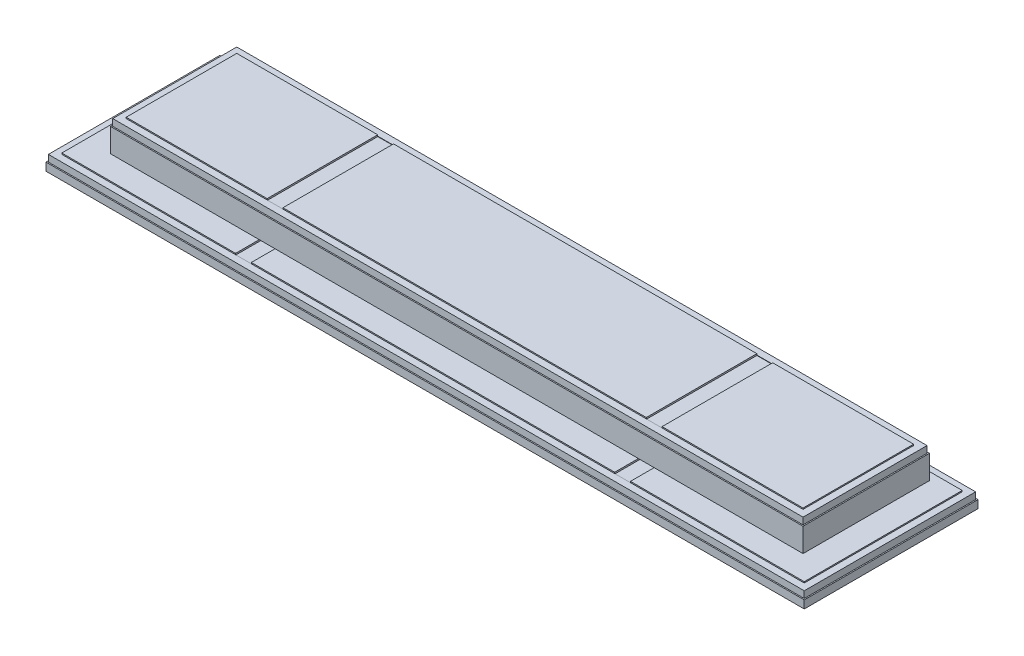
SolidWorks part; units mm, degrees
ref_plane "Front Plane" through (0, 0, 0) normal (0, 0, 1) x (1, 0, 0)
ref_plane "Top Plane" through (0, 0, 0) normal (0, 1, 0) x (1, 0, 0)
ref_plane "Right Plane" through (0, 0, 0) normal (1, 0, 0) x (0, 0, -1)
sketch "Sketch1" plane through (0, 0, 0) normal (0, 1, 0) x (1, 0, 0)
  line L0 (960, -210) -> (-960, -210)
  line L5 (960, -210) -> (960, 230)
  line L6 (-960, -210) -> (-960, 230)
  line L10 (960, 230) -> (-960, 230)
  point P0 (0, 0)
extrude "Boss-Extrude1" add sketch "Sketch1" along normal blind 40
ref_plane "Plane1" through (0, 40, 0) normal (0, 1, 0) x (1, 0, 0)
sketch "Sketch4" plane through (0, 40, 0) normal (0, 1, 0) x (1, 0, 0)
  line L7 (-960, -130) -> (960, -130)
  line L8 (-877, -130) -> (877, -130)
  line L13 (-877, 230) -> (-877, -210)
  line L14 (-877, 190) -> (-877, -130)
  line L17 (877, -210) -> (877, 230)
  line L19 (877, -130) -> (877, 190)
  line L21 (960, 190) -> (-960, 190)
  line L22 (877, 190) -> (-877, 190)
  dimension "D1" = 80
  dimension "D2" = 83
  dimension "D3" = 83
  dimension "D4" = 40
extrude "Boss-Extrude2" add sketch "Sketch4" along normal blind 80
ref_plane "Plane2" through (0, 120, 0) normal (0, 1, 0) x (1, 0, 0)
sketch "Sketch5" plane through (0, 120, 0) normal (0, 1, 0) x (1, 0, 0)
  line L0 (-857, -110) -> (857, -110)
  line L1 (857, -110) -> (857, 170)
  line L2 (857, 170) -> (-857, 170)
  line L3 (-857, 170) -> (-857, -110)
  line L4 (877, -130) -> (877, 190)
  line L5 (877, 190) -> (-877, 190)
  line L6 (-877, 190) -> (-877, -130)
  line L7 (-877, -130) -> (877, -130)
  line L8 (877, -130) -> (877, 190)
  line L9 (877, 190) -> (-877, 190)
  line L10 (-877, 190) -> (-877, -130)
  line L11 (-877, -130) -> (877, -130)
  dimension "D1" = 0
  dimension "D2" = 20
extrude "Cut-Extrude1" cut sketch "Sketch5" against normal blind 3
sketch "Sketch6" plane through (0, 120, 0) normal (0, 1, 0) x (1, 0, 0)
  line L0 (-874, -127) -> (874, -127)
  line L1 (874, -127) -> (874, 187)
  line L2 (874, 187) -> (-874, 187)
  line L3 (-874, 187) -> (-874, -127)
  line L4 (-877, -130) -> (877, -130)
  line L5 (877, -130) -> (877, 190)
  line L6 (877, 190) -> (-877, 190)
  line L7 (-877, 190) -> (-877, -130)
  line L8 (-877, -130) -> (877, -130)
  line L9 (877, -130) -> (877, 190)
  line L10 (877, 190) -> (-877, 190)
  line L11 (-877, 190) -> (-877, -130)
  dimension "D1" = 0
  dimension "D2" = 3
extrude "Cut-Extrude2" cut sketch "Sketch6" against normal blind 20
sketch "Sketch7" plane through (0, 120, 0) normal (0, 1, 0) x (1, 0, 0)
  line L0 (857, -110) -> (857, 170) construction
  line L1 (857, -110) -> (857, 170) construction
  line L2 (-857, 170) -> (-857, -110) construction
  line L3 (-857, 170) -> (-857, -110) construction
  line L4 (500, -110) -> (500, 170)
  line L5 (-500, 170) -> (-500, -110)
  line L6 (460, -110) -> (460, 170)
  line L7 (-460, 170) -> (-460, -110)
  line L8 (500, -110) -> (460, -110)
  line L9 (500, 170) -> (460, 170)
  line L10 (-460, -110) -> (-500, -110)
  line L11 (-460, 170) -> (-500, 170)
  dimension "D1" = 357
  dimension "D2" = 40
extrude "Cut-Extrude3" cut sketch "Sketch7" against normal blind 4
ref_plane "Plane3" through (0, 40, 0) normal (0, 1, 0) x (1, 0, 0)
ref_plane "Plane4" through (0, 40, 0) normal (0, 1, 0) x (1, 0, 0)
sketch "Sketch8" plane through (0, 40, 0) normal (0, 1, 0) x (1, 0, 0)
  line L0 (-960, 230) -> (-960, -210) construction
  line L1 (960, 230) -> (-960, 230) construction
  line L2 (960, -210) -> (960, 230) construction
  line L3 (-960, -210) -> (960, -210) construction
  line L4 (-960, 230) -> (-960, -210)
  line L5 (960, 230) -> (-960, 230)
  line L6 (960, -210) -> (960, 230)
  line L7 (-960, -210) -> (960, -210)
  line L8 (-940, -190) -> (940, -190)
  line L9 (940, -190) -> (940, 210)
  line L10 (940, 210) -> (-940, 210)
  line L11 (-940, 210) -> (-940, -190)
  dimension "D1" = 20
extrude "Cut-Extrude4" cut sketch "Sketch8" against normal blind 3
sketch "Sketch9" plane through (0, 40, 0) normal (0, 1, 0) x (1, 0, 0)
  line L0 (960, 230) -> (-960, 230) construction
  line L1 (-960, 230) -> (-960, -210) construction
  line L2 (960, -210) -> (960, 230) construction
  line L3 (-960, -210) -> (960, -210) construction
  line L4 (960, 230) -> (-960, 230)
  line L5 (-960, 230) -> (-960, -210)
  line L6 (960, -210) -> (960, 230)
  line L7 (-960, -210) -> (960, -210)
  line L8 (957, 227) -> (-957, 227)
  line L9 (-957, 227) -> (-957, -207)
  line L10 (-957, -207) -> (957, -207)
  line L11 (957, -207) -> (957, 227)
  dimension "D1" = 3
extrude "Cut-Extrude5" cut sketch "Sketch9" against normal blind 20
sketch "Sketch10" plane through (0, 40, 0) normal (0, 1, 0) x (1, 0, 0)
  line L1 (-500, 170) -> (-500, -110) construction
  line L3 (-460, -110) -> (-460, 170) construction
  line L5 (500, -110) -> (500, 170) construction
  line L7 (460, 170) -> (460, -110) construction
  line L9 (-500, 210) -> (-500, -190)
  line L11 (-460, -190) -> (-460, 210)
  line L13 (500, -190) -> (500, 210)
  line L15 (460, 210) -> (460, -190)
  line L16 (-940, -190) -> (940, -190) construction
  line L17 (-500, -190) -> (-460, -190)
  line L18 (940, 210) -> (-940, 210) construction
  line L19 (500, 210) -> (460, 210)
  line L20 (460, -190) -> (500, -190)
  line L21 (-460, 210) -> (-500, 210)
extrude "Cut-Extrude9" cut sketch "Sketch10" against normal blind 4
